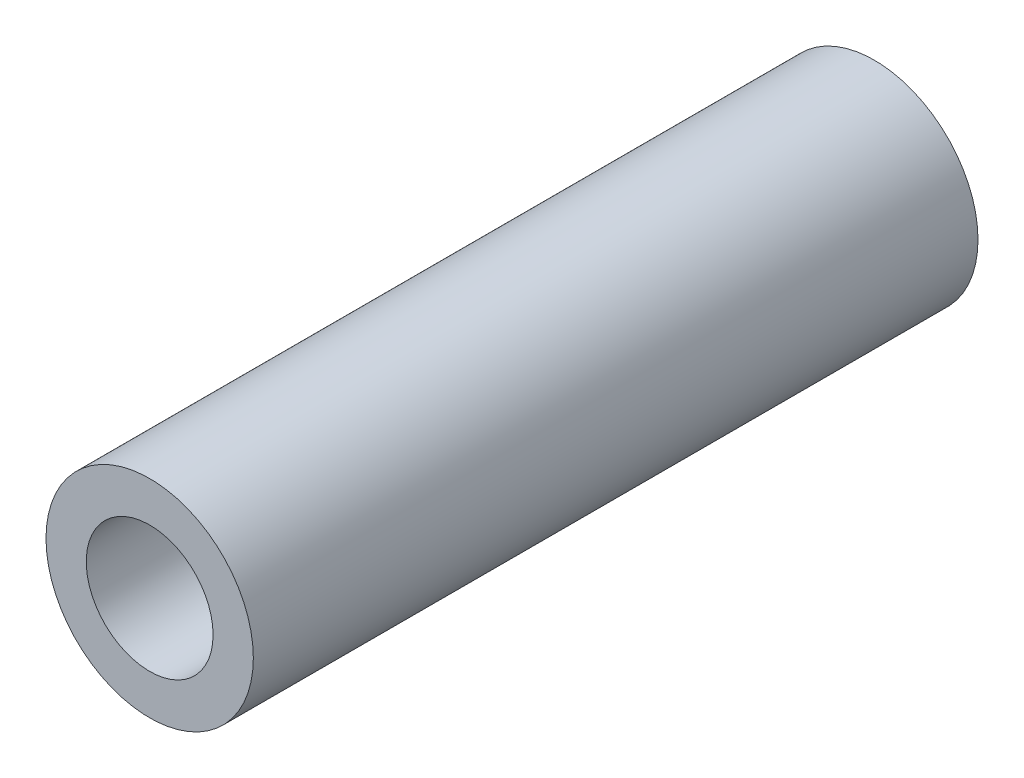
SolidWorks part; units mm, degrees
material "ABS"
ref_plane "Front Plane" through (0, 0, 0) normal (0, 0, 1) x (1, 0, 0)
ref_plane "Top Plane" through (0, 0, 0) normal (0, 1, 0) x (1, 0, 0)
ref_plane "Right Plane" through (0, 0, 0) normal (1, 0, 0) x (0, 0, -1)
sketch "Sketch1" plane through (0, 0, 0) normal (0, 0, 1) x (1, 0, 0)
  circle A0 centre (32.5, 0) radius 2.575
  dimension "D1" = 5.15
extrude "Boss-Extrude1" add sketch "Sketch1" along normal blind 18
sketch "Sketch3" plane through (0, 0, 18) normal (0, 0, 1) x (1, 0, 0)
  circle A0 centre (32.5, 0) radius 1.575
  circle A1 centre (32.5, 0) radius 2.1
  dimension "D1" = 3.15
  dimension "D2" = 4.2
extrude "Cut-Extrude1" cut sketch "Sketch3" against normal up to next contours A0
equation "\"RingPostIn\"=5.15"
equation "\"D1@Sketch1\"=\"RingPostIn\""
equation "\"RingPinShaft\"= 5.05"
equation "\"CenterBearingOut\"=32.00"
equation "\"m3Thru\"=3.15"
equation "\"D1@Sketch3\"=\"m3Thru\""
equation "\"m3Insert\"=4.2"
equation "\"D2@Sketch3\"=\"m3Insert\""
